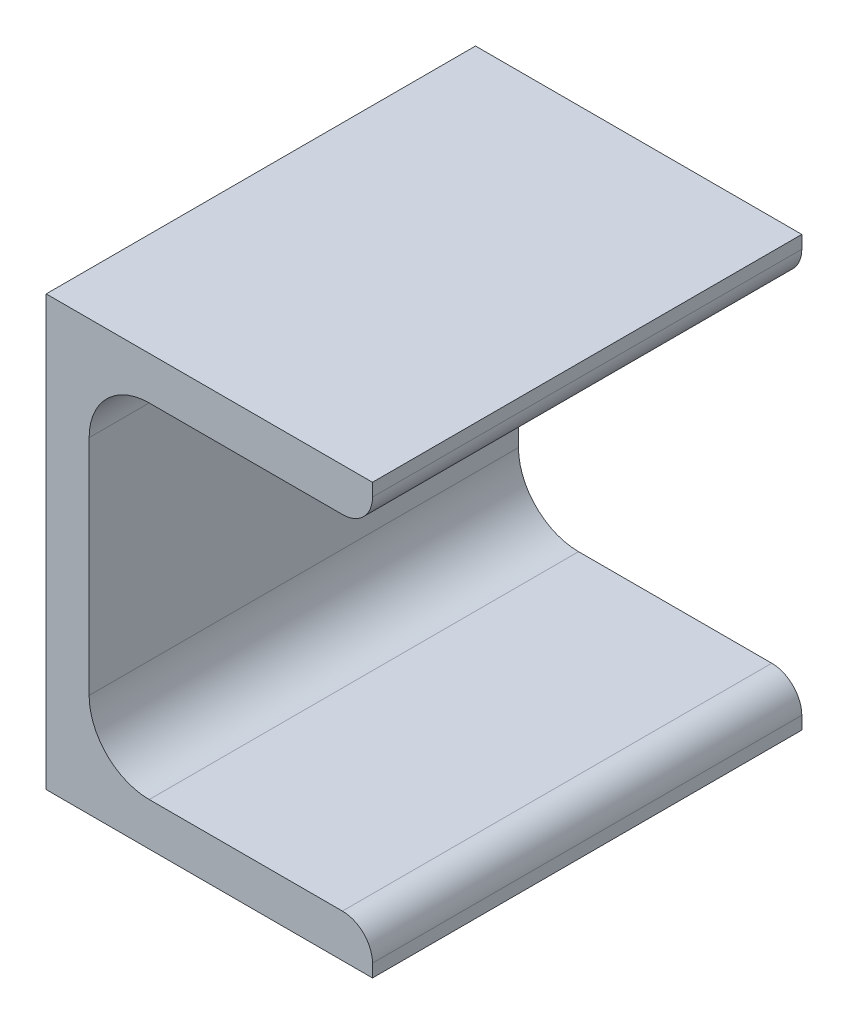
SolidWorks part; units mm, degrees
material "1.0037 (S235JR)"
ref_plane "Płaszczyzna przednia" through (0, 0, 0) normal (0, 0, 1) x (1, 0, 0)
ref_plane "Płaszczyzna górna" through (0, 0, 0) normal (0, 1, 0) x (1, 0, 0)
ref_plane "Płaszczyzna prawa" through (0, 0, 0) normal (1, 0, 0) x (0, 0, -1)
sketch "Szkic1" plane through (0, 0, 0) normal (0, 0, 1) x (1, 0, 0)
  line L0 (0, 0) -> (0, -50)
  line L1 (0, -50) -> (38, -50)
  line L2 (38, -50) -> (38, -48.5)
  line L3 (34.5, -45) -> (12, -45)
  line L4 (5, -38) -> (5, -12)
  line L5 (12, -5) -> (34.5, -5)
  line L6 (38, -1.5) -> (38, 0)
  line L7 (38, 0) -> (0, 0)
  arc A0 (12, -45) -> (5, -38) centre (12, -38) cw
  arc A1 (5, -12) -> (12, -5) centre (12, -12) cw
  arc A2 (38, -48.5) -> (34.5, -45) centre (34.5, -48.5) ccw
  arc A3 (34.5, -5) -> (38, -1.5) centre (34.5, -1.5) ccw
  dimension "D7" = 7
  dimension "D8" = 3.5
  dimension "D1" = 50
  dimension "D2" = 38
  dimension "D3" = 38
  dimension "D4" = 5
  dimension "D5" = 5
  dimension "D6" = 5
extrude "Dodanie-wyciągnięcie1" add sketch "Szkic1" along normal blind 50
